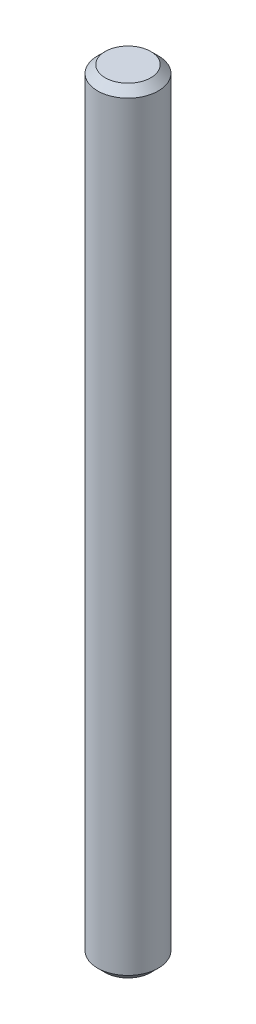
SolidWorks part; units mm, degrees
ref_plane "前视基准面" through (0, 0, 0) normal (0, 0, 1) x (1, 0, 0)
ref_plane "上视基准面" through (0, 0, 0) normal (0, 1, 0) x (1, 0, 0)
ref_plane "右视基准面" through (0, 0, 0) normal (1, 0, 0) x (0, 0, -1)
sketch "草图1" plane through (0, 0, 0) normal (0, 1, 0) x (1, 0, 0)
  circle A0 centre (0.5674, 0.5932) radius 2
  dimension "D1" = 4
extrude "凸台-拉伸1" add sketch "草图1" along normal blind 51
cosmetic thread "装饰螺纹线1" parameters "D1"=3, "D2"=3.242
cosmetic thread "装饰螺纹线2" parameters "D1"=3, "D2"=3.242
chamfer "倒角1" distance 0.5 angle 45 2 edges at (0.5674, 0, 1.4068) (0.5674, 51, 1.4068)
